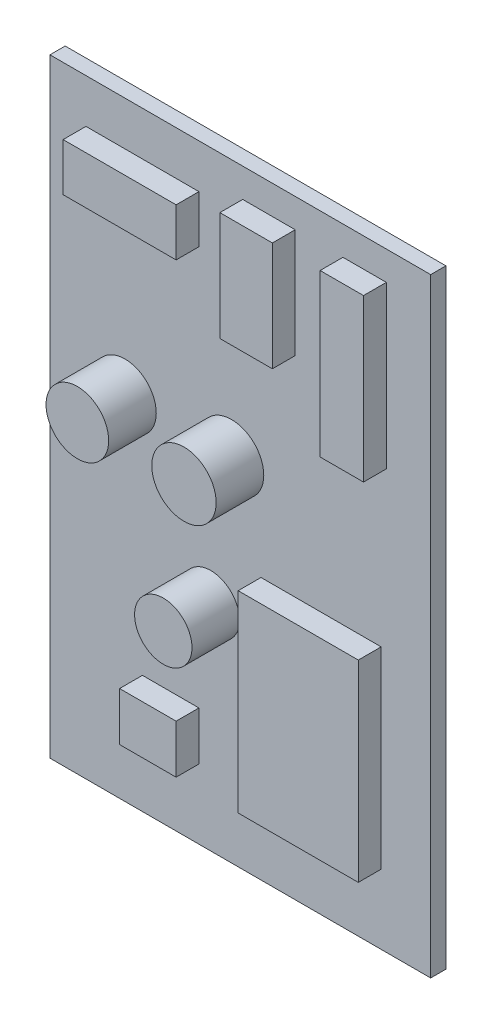
SolidWorks part; units mm, degrees
ref_plane "Front Plane" through (0, 0, 0) normal (0, 0, 1) x (1, 0, 0)
ref_plane "Top Plane" through (0, 0, 0) normal (0, 1, 0) x (1, 0, 0)
ref_plane "Right Plane" through (0, 0, 0) normal (1, 0, 0) x (0, 0, -1)
sketch "Sketch1" plane through (0, 0, 0) normal (0, 0, 1) x (1, 0, 0)
  line L1 (-22.4425, 17.4842) -> (2.9575, 17.4842)
  line L2 (-22.4425, 17.4842) -> (-22.4425, -23.1558)
  line L3 (-22.4425, -23.1558) -> (2.9575, -23.1558)
  line L4 (2.9575, 17.4842) -> (2.9575, -23.1558)
  dimension "D1" = 25.4
  dimension "D2" = 40.64
extrude "Boss-Extrude1" add sketch "Sketch1" along normal blind 1.016
sketch "Sketch4" plane through (0, 0, 1.016) normal (0, 0, 1) x (1, 0, 0)
  circle A0 centre (-17.4395, 0.3227) radius 2.0892
  circle A1 centre (-10.3264, 0.3227) radius 2.1477
  circle A2 centre (-11.7065, -8.8606) radius 1.9139
extrude "Boss-Extrude3" add sketch "Sketch4" along normal blind 3.175
sketch "Sketch3" plane through (0, 0, 0) normal (0, 0, 1) x (1, 0, 0)
  line L1 (-2.8948, 15.5574) -> (0, 15.5574)
  line L2 (-2.8948, 15.5574) -> (-2.8948, 4.7816)
  line L3 (-2.8948, 4.7816) -> (0, 4.7816)
  line L4 (0, 15.5574) -> (0, 4.7816)
  line L5 (-9.5832, 15.5574) -> (-6.0798, 15.5574)
  line L6 (-9.5832, 15.5574) -> (-9.5832, 8.2851)
  line L7 (-9.5832, 8.2851) -> (-6.0798, 8.2851)
  line L8 (-6.0798, 15.5574) -> (-6.0798, 8.2851)
  line L9 (-20.0405, 14.5488) -> (-12.5028, 14.5488)
  line L10 (-20.0405, 14.5488) -> (-20.0405, 11.3639)
  line L11 (-20.0405, 11.3639) -> (-12.5028, 11.3639)
  line L12 (-12.5028, 14.5488) -> (-12.5028, 11.3639)
  line L13 (-16.2716, -15.2836) -> (-12.5028, -15.2836)
  line L14 (-16.2716, -15.2836) -> (-16.2716, -18.5217)
  line L15 (-16.2716, -18.5217) -> (-12.5028, -18.5217)
  line L16 (-12.5028, -15.2836) -> (-12.5028, -18.5217)
  line L17 (-8.3623, -5.6757) -> (-0.3468, -5.6757)
  line L18 (-8.3623, -5.6757) -> (-8.3623, -18.5217)
  line L19 (-8.3623, -18.5217) -> (-0.3468, -18.5217)
  line L20 (-0.3468, -5.6757) -> (-0.3468, -18.5217)
extrude "Boss-Extrude2" add sketch "Sketch3" along normal blind 2.54
